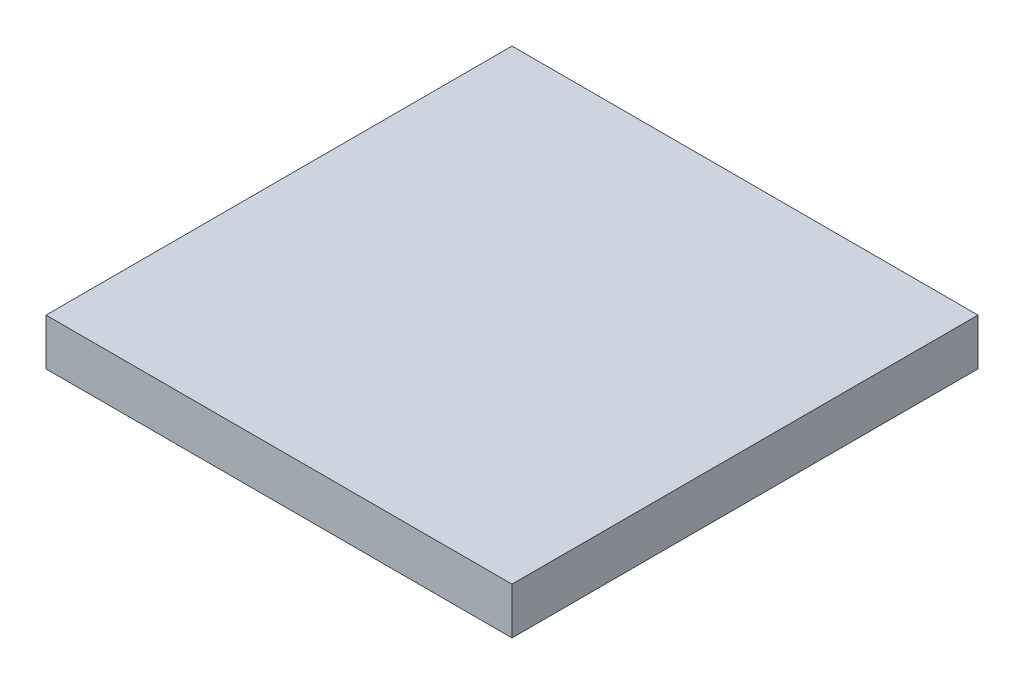
SolidWorks part; units mm, degrees
ref_plane "Front Plane" through (0, 0, 0) normal (0, 0, 1) x (1, 0, 0)
ref_plane "Top Plane" through (0, 0, 0) normal (0, 1, 0) x (1, 0, 0)
ref_plane "Right Plane" through (0, 0, 0) normal (1, 0, 0) x (0, 0, -1)
sketch "Sketch1" plane through (0, 0, 0) normal (0, 1, 0) x (1, 0, 0)
  line L1 (0, 0) -> (5, 0)
  line L2 (0, 0) -> (0, 5)
  line L3 (0, 5) -> (5, 5)
  line L4 (5, 0) -> (5, 5)
  dimension "D1" = 5
  dimension "D2" = 5
extrude "Boss-Extrude1" add sketch "Sketch1" along normal blind 0.5
